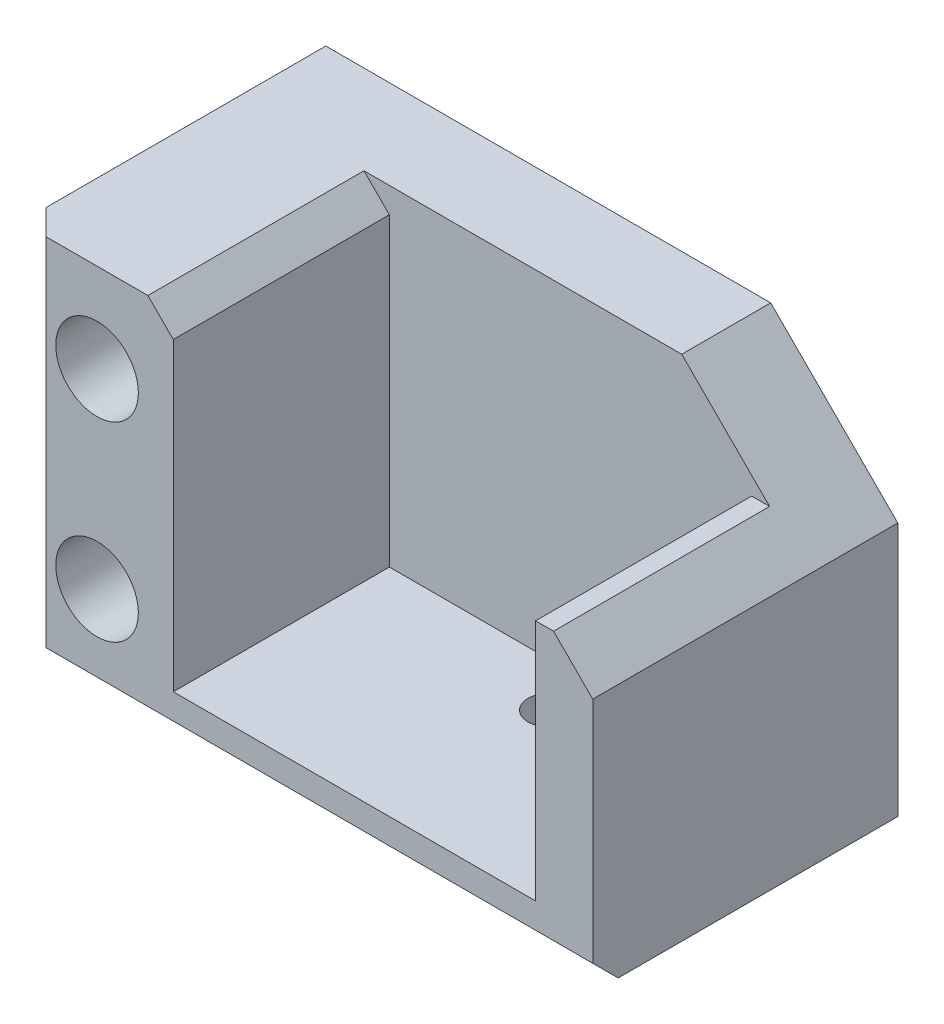
SolidWorks part; units mm, degrees
ref_plane "Спереди" through (0, 0, 0) normal (0, 0, 1) x (1, 0, 0)
ref_plane "Сверху" through (0, 0, 0) normal (0, 1, 0) x (1, 0, 0)
ref_plane "Справа" through (0, 0, 0) normal (1, 0, 0) x (0, 0, -1)
ref_plane "Плоскость4" through (0, 0, 21) normal (0, 0, 1) x (1, 0, 0)
sketch "Эскиз1" plane through (0, 0, 21) normal (0, 0, 1) x (1, 0, 0)
  line L0 (51, 6) -> (51, 36)
  line L1 (51, 36) -> (6, 36)
  line L2 (6, 36) -> (6, 6)
  line L3 (6, 6) -> (51, 6)
extrude "Бобышка-Вытянуть1" add sketch "Эскиз1" against normal blind 24
sketch "Эскиз2" plane through (51, 0, 0) normal (1, 0, 0) x (0, 0, -1)
  line L0 (-4, 29.0858) -> (-4, 36)
  line L1 (-4, 36) -> (-21, 36)
  line L2 (-21, 36) -> (-21, 29.0858)
  line L3 (-21, 29.0858) -> (-4, 29.0858)
extrude "Вырез-Вытянуть1" cut sketch "Эскиз2" against normal blind 33
ref_plane "Плоскость5" through (0, 29.0858, 0) normal (0, 1, 0) x (1, 0, 0)
ref_plane "Плоскость6" through (0, 10, 0) normal (0, -1, 0) x (1, 0, 0)
sketch "Эскиз4" plane through (0, 10, 0) normal (0, -1, 0) x (1, 0, 0)
  line L0 (18, 21) -> (18, 4)
  line L1 (18, 4) -> (46.5, 4)
  line L2 (46.5, 4) -> (46.5, 21)
  line L3 (46.5, 21) -> (18, 21)
extrude "Вырез-Вытянуть2" cut sketch "Эскиз4" against normal up to surface up to plane "Плоскость5"
hole_wizard "Диаметр отверстия Ø3.2 (3.2)1" positions "Эскиз6" profile "Эскиз5" hole size "Ø3.2" standard "Ansi Metric"
sketch "Эскиз6" plane through (0, 0, 4) normal (0, 0, 1) x (1, 0, 0)
  point P0 (42, 14)
sketch "Эскиз5" plane through (42, 14, 4) normal (1, 0, 0) x (0, -1, 0)
  line L0 (0, 0) -> (0, 7)
  line L1 (0, 7) -> (1.6, 7)
  line L2 (1.6, 7) -> (1.6, 0)
  line L5 (1.6, 0) -> (0, 0)
  line L11 (0, -6.35) -> (0, 107.95) construction
  dimension "Диаметр сквозного отверстия" = 3.2
  dimension "Глубина сквозного отверстия" = 7
hole_wizard "Диаметр отверстия Ø3.2 (3.2)2" positions "Эскиз8" profile "Эскиз7" hole size "Ø3.2" standard "Ansi Metric"
sketch "Эскиз8" plane through (0, 10, 0) normal (0, 1, 0) x (1, 0, 0)
  point P0 (34, -7.5)
sketch "Эскиз7" plane through (34, 10, 7.5) normal (1, 0, 0) x (0, 0, 1)
  line L0 (0, 0) -> (0, 4)
  line L1 (0, 4) -> (1.6, 4)
  line L2 (1.6, 4) -> (1.6, 0)
  line L5 (1.6, 0) -> (0, 0)
  line L11 (0, -6.35) -> (0, 107.95) construction
  dimension "Диаметр сквозного отверстия" = 3.2
  dimension "Глубина сквозного отверстия" = 4
hole_wizard "Цековка для винта с заклепочной головкой M31" positions "Эскиз10" profile "Эскиз9" counterbore size "M3" standard "Ansi Metric"
sketch "Эскиз10" plane through (0, 0, 21) normal (0, 0, 1) x (1, 0, 0)
  point P0 (12, 29)
  point P1 (12, 14)
sketch "Эскиз9" plane through (12, 29, 21) normal (1, 0, 0) x (0, -1, 0)
  line L0 (0, 0) -> (0, 24)
  line L1 (0, 24) -> (1.7, 24)
  line L3 (1.7, 24) -> (1.7, 15)
  line L4 (1.7, 15) -> (3.25, 15)
  line L5 (3.25, 15) -> (3.25, 0)
  line L7 (3.25, 0) -> (0, 0)
  line L11 (0, -6.35) -> (0, 107.95) construction
  dimension "Диаметр сквозного отверстия" = 3.4
  dimension "Глубина сквозного отверстия" = 24
  dimension "Диаметр цековки" = 6.5
  dimension "Глубина цековки" = 15
chamfer "Фаска1" distance 2 angle 45 3 edges at (6, 21, 21) (28.5, 6, 21) (18, 36, 12.5)
chamfer "Фаска2" distance 10 angle 45 1 edges at (51, 36, 0.5)
